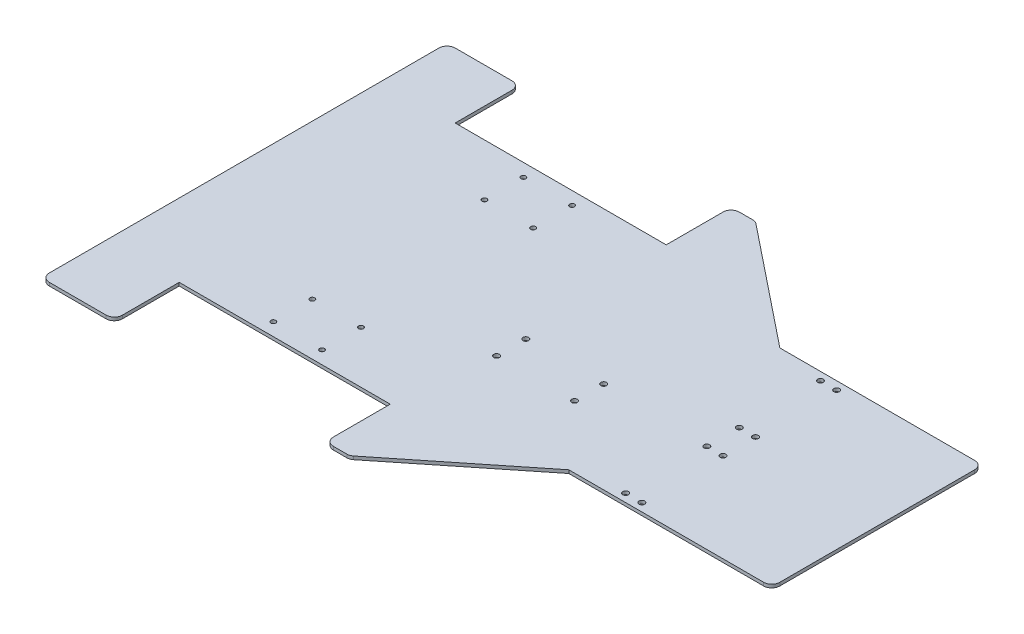
SolidWorks part; units mm, degrees
ref_plane "정면" through (0, 0, 0) normal (0, 0, 1) x (1, 0, 0)
ref_plane "윗면" through (0, 0, 0) normal (0, 1, 0) x (1, 0, 0)
ref_plane "우측면" through (0, 0, 0) normal (1, 0, 0) x (0, 0, -1)
sketch "스케치1" plane through (0, 0, 0) normal (0, 1, 0) x (1, 0, 0)
  line L1 (-195, -125) -> (195, -125)
  line L2 (-195, -125) -> (-195, 125)
  line L3 (-195, 125) -> (195, 125)
  line L4 (195, -125) -> (195, 125)
  line L5 (-195, -125) -> (195, 125) construction
  line L6 (-195, 125) -> (195, -125) construction
  point P0 (0, 0)
  dimension "D1" = 390
  dimension "D2" = 250
extrude "보스-돌출1" add sketch "스케치1" along normal blind 2
sketch "스케치2" plane through (0, 2, 0) normal (0, 1, 0) x (1, 0, 0)
  line L5 (195, 125) -> (-195, 125) construction
  line L6 (-150, 125) -> (-20, 125)
  line L7 (-150, 125) -> (-150, 85)
  line L8 (-150, 85) -> (-20, 85)
  line L9 (-20, 125) -> (-20, 85)
  line L10 (-150, -125) -> (-20, -125)
  line L11 (-150, -125) -> (-150, -85)
  line L12 (-150, -85) -> (-20, -85)
  line L13 (-20, -125) -> (-20, -85)
  line L14 (-195, -125) -> (195, -125) construction
  line L15 (70, 125) -> (195, 125)
  line L16 (70, 125) -> (70, 65)
  line L17 (70, 65) -> (195, 65)
  line L18 (195, 125) -> (195, 65)
  line L19 (70, -125) -> (195, -125)
  line L20 (70, -125) -> (70, -65)
  line L21 (70, -65) -> (195, -65)
  line L22 (195, -125) -> (195, -65)
  line L23 (195, -125) -> (195, 125) construction
  line L24 (-195, 125) -> (-195, -125) construction
  dimension "D1" = 130
  dimension "D2" = 40
  dimension "D3" = 40
  dimension "D4" = 60
  dimension "D5" = 60
  dimension "D6" = 45
  dimension "D7" = 125
extrude "컷-돌출1" cut sketch "스케치2" against normal blind 5
sketch "스케치3" plane through (0, 2, 0) normal (0, 1, 0) x (1, 0, 0)
  line L0 (-5, 125) -> (70, 65)
  line L2 (70, -65) -> (-5, -125)
  line L4 (-5, 125) -> (70, 125)
  line L5 (-5, -125) -> (70, -125)
  line L6 (70, -65) -> (70, -125)
  line L7 (70, 65) -> (70, 125)
  dimension "D1" = 75
  dimension "D2" = 75
extrude "컷-돌출2" cut sketch "스케치3" against normal blind 10
fillet "필렛1" radius 5 10 edges at (-20, 1, 125) (-20, 1, -125) (-5, 1, 125) (-5, 1, -125) (195, 1, -65) (195, 1, 65) (-195, 1, -125) (-195, 1, 125) (-150, 1, -125) (-150, 1, 125)
sketch "스케치4" plane through (0, 2, 0) normal (0, 1, 0) x (1, 0, 0)
  line L0 (-195, 0) -> (195, 0) construction
  line L1 (-100, 77) -> (-70, 77) construction
  line L2 (-100, 77) -> (-100, 53) construction
  line L3 (-100, 53) -> (-70, 53) construction
  line L4 (-70, 77) -> (-70, 53) construction
  line L5 (-100, 77) -> (-70, 53) construction
  line L6 (-100, 53) -> (-70, 77) construction
  line L7 (-195, 120) -> (-195, -120) construction
  line L8 (195, -60) -> (195, 60) construction
  line L9 (-150, 85) -> (-20, 85) construction
  line L10 (-100, -53) -> (-70, -77) construction
  line L11 (-100, -77) -> (-70, -53) construction
  line L12 (-70, -77) -> (-70, -53) construction
  line L13 (-100, -53) -> (-70, -53) construction
  line L14 (-100, -77) -> (-100, -53) construction
  line L15 (-100, -77) -> (-70, -77) construction
  line L17 (100, -60) -> (110, -60) construction
  line L18 (100, -60) -> (100, 60) construction
  line L19 (100, 60) -> (110, 60) construction
  line L20 (110, -60) -> (110, 60) construction
  line L21 (100, -60) -> (110, 60) construction
  line L22 (100, 60) -> (110, -60) construction
  line L23 (100, -10) -> (110, -10) construction
  line L24 (100, -10) -> (100, 10) construction
  line L25 (100, 10) -> (110, 10) construction
  line L26 (110, -10) -> (110, 10) construction
  line L27 (100, -10) -> (110, 10) construction
  line L28 (100, 10) -> (110, -10) construction
  circle A0 centre (-100, 77) radius 1.5
  circle A1 centre (-70, 77) radius 1.5
  circle A2 centre (-70, 53) radius 1.5
  circle A3 centre (-100, 53) radius 1.5
  circle A4 centre (-100, -53) radius 1.5
  circle A5 centre (-70, -53) radius 1.5
  circle A6 centre (-70, -77) radius 1.5
  circle A7 centre (-100, -77) radius 1.5
  circle A8 centre (100, 60) radius 1.75
  circle A9 centre (110, 60) radius 1.75
  circle A10 centre (100, 10) radius 1.75
  circle A11 centre (110, 10) radius 1.75
  circle A12 centre (100, -10) radius 1.75
  circle A13 centre (110, -10) radius 1.75
  circle A14 centre (100, -60) radius 1.75
  circle A15 centre (110, -60) radius 1.75
  point P0 (-85, 65)
  point P25 (-85, -65)
  point P26 (105, 0)
  point P31 (105, 0)
  dimension "D5" = 3
  dimension "D9" = 3.5
  dimension "D1" = 30
  dimension "D2" = 24
  dimension "D3" = 95
  dimension "D4" = 32
  dimension "D6" = 120
  dimension "D7" = 10
  dimension "D8" = 20
  dimension "D10" = 85
extrude "컷-돌출3" cut sketch "스케치4" against normal through all
sketch "스케치5" plane through (0, 2, 0) normal (0, 1, 0) x (1, 0, 0)
  line L0 (-20, -85) -> (-150, -85) construction
  line L1 (-13, -26.5) -> (35, -26.5) construction
  line L2 (-13, -26.5) -> (-13, -8.5) construction
  line L3 (-13, -8.5) -> (35, -8.5) construction
  line L4 (35, -26.5) -> (35, -8.5) construction
  line L5 (195, -60) -> (195, 60) construction
  circle A1 centre (-13, -8.5) radius 1.75
  circle A2 centre (35, -8.5) radius 1.75
  circle A3 centre (-13, -26.5) radius 1.75
  circle A4 centre (35, -26.5) radius 1.75
  dimension "D1" = 3.5
  dimension "D2" = 58.5
  dimension "D3" = 18
  dimension "D4" = 48
  dimension "D5" = 160
extrude "컷-돌출4" cut sketch "스케치5" against normal through all
